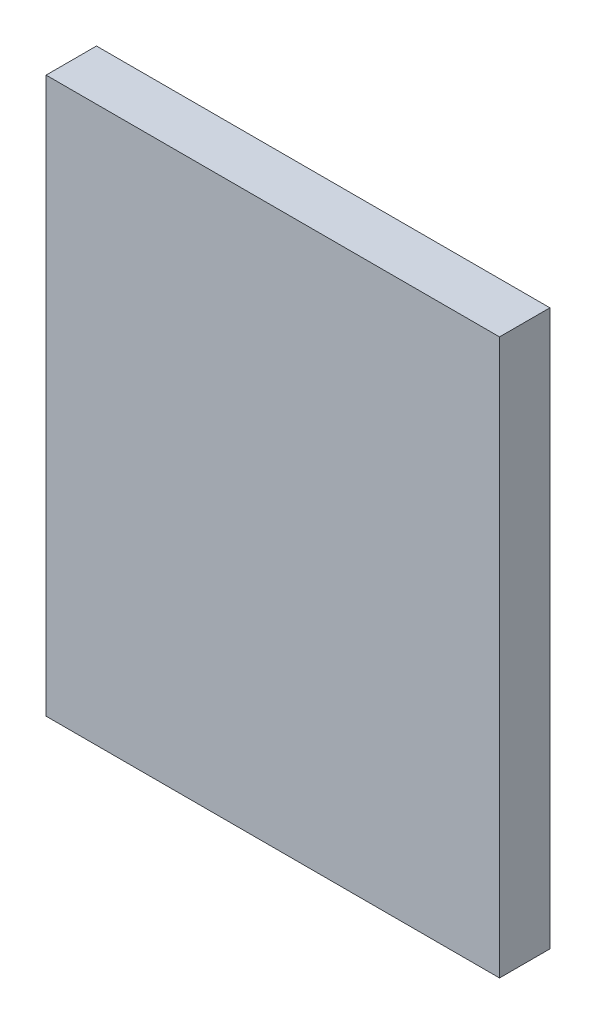
SolidWorks part; units mm, degrees
ref_plane "Front Plane" through (0, 0, 0) normal (0, 0, 1) x (1, 0, 0)
ref_plane "Top Plane" through (0, 0, 0) normal (0, 1, 0) x (1, 0, 0)
ref_plane "Right Plane" through (0, 0, 0) normal (1, 0, 0) x (0, 0, -1)
sketch "Sketch1" plane through (0, 0, 0) normal (0, 0, 1) x (1, 0, 0)
  line L1 (0, 0) -> (228.6, 0)
  line L2 (0, 0) -> (0, 279.908)
  line L3 (0, 279.908) -> (228.6, 279.908)
  line L4 (228.6, 0) -> (228.6, 279.908)
  dimension "D1" = 228.6
  dimension "D2" = 279.908
extrude "Boss-Extrude1" add sketch "Sketch1" along normal mid plane 25.4
